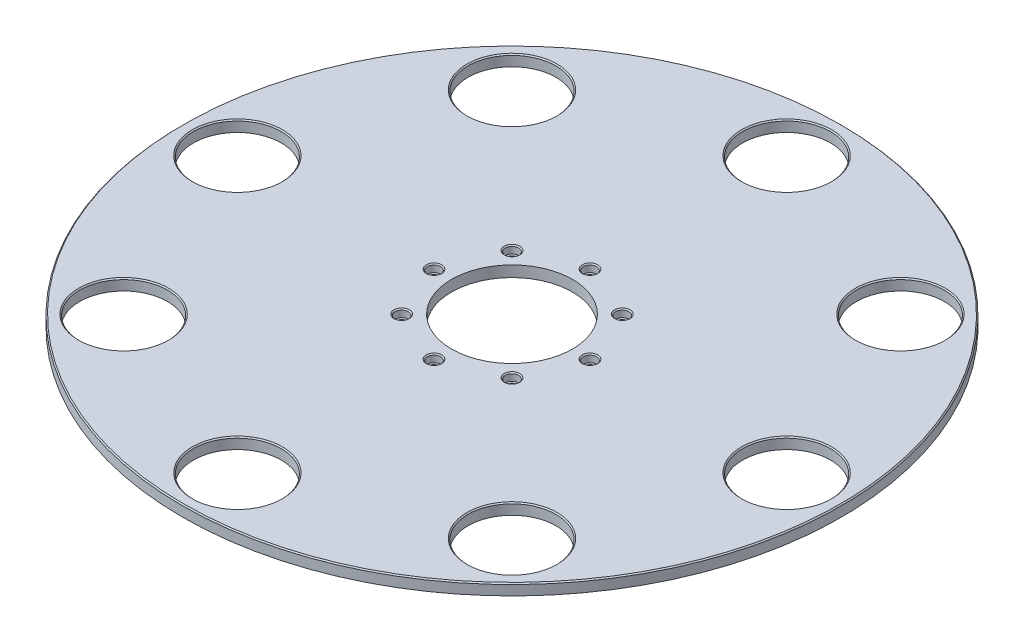
SolidWorks part; units mm, degrees
ref_plane "Front Plane" through (0, 0, 0) normal (0, 0, 1) x (1, 0, 0)
ref_plane "Top Plane" through (0, 0, 0) normal (0, 1, 0) x (1, 0, 0)
ref_plane "Right Plane" through (0, 0, 0) normal (1, 0, 0) x (0, 0, -1)
sketch "Sketch2" plane through (0, 0, 0) normal (0, 1, 0) x (1, 0, 0)
  line L0 (0, 409.7546) -> (0, -366.7272) construction
  line L1 (-380.7051, 0) -> (447.7899, 0) construction
  circle A0 centre (0, 0) radius 300
  circle A1 centre (0, 0) radius 55
  circle A2 centre (0, 250) radius 40
  circle A3 centre (176.7767, 176.7767) radius 40
  circle A4 centre (250, 0) radius 40
  circle A5 centre (176.7767, -176.7767) radius 40
  circle A6 centre (0, -250) radius 40
  circle A7 centre (-176.7767, -176.7767) radius 40
  circle A8 centre (-250, 0) radius 40
  circle A9 centre (-176.7767, 176.7767) radius 40
  point P26 (0, 0)
  point P52 (0, 0)
  dimension "D1" = 250
  dimension "D2" = 110
  dimension "D3" = 80
  dimension "D5" = 600
  dimension "D4" = 8
extrude "Boss-Extrude10" add sketch "Sketch2" along normal blind 10
chamfer "Chamfer1" distance 1 angle 45 9 edges at (-176.7767, 10, 216.7767) (0, 10, 290) (176.7767, 10, 216.7767) (250, 10, 40) (176.7767, 10, -136.7767) (0, 10, -210) (-176.7767, 10, -136.7767) (-250, 10, 40) (0, 10, 300)
sketch "Sketch13" plane through (0, 10, 0) normal (0, 1, 0) x (1, 0, 0)
  line L0 (0, 0) -> (-373.6419, 0) construction
  circle A0 centre (-71, 0) radius 6
  circle A1 centre (-50.2046, 50.2046) radius 6
  circle A2 centre (0, 71) radius 6
  circle A3 centre (50.2046, 50.2046) radius 6
  circle A4 centre (71, 0) radius 6
  circle A5 centre (50.2046, -50.2046) radius 6
  circle A6 centre (0, -71) radius 6
  circle A7 centre (-50.2046, -50.2046) radius 6
  point P6 (-64.3571, 54.9732)
  point P7 (0, 0)
  point P21 (0, 0)
  dimension "D1" = 71
  dimension "D2" = 12
  dimension "D3" = 8
extrude "Cut-Extrude1" cut sketch "Sketch13" against normal blind 7
sketch "Sketch14" plane through (0, 0, 0) normal (0, -1, 0) x (1, 0, 0)
  line L0 (0, 0) -> (-132.8482, 0) construction
  circle A0 centre (-71, 0) radius 4
  circle A1 centre (-50.2046, 50.2046) radius 4
  circle A2 centre (0, 71) radius 4
  circle A3 centre (50.2046, 50.2046) radius 4
  circle A4 centre (71, 0) radius 4
  circle A5 centre (50.2046, -50.2046) radius 4
  circle A6 centre (0, -71) radius 4
  circle A7 centre (-50.2046, -50.2046) radius 4
  point P6 (-60.629, 54.5027)
  point P7 (0, 0)
  point P21 (0, 0)
  dimension "D1" = 71
  dimension "D2" = 8
  dimension "D3" = 8
extrude "Cut-Extrude2" cut sketch "Sketch14" against normal blind 3
chamfer "Chamfer2" distance 1 angle 45 8 edges at (0, 10, 77) (50.2046, 10, 56.2046) (71, 10, 6) (50.2046, 10, -44.2046) (0, 10, -65) (-50.2046, 10, -44.2046) (-71, 10, 6) (-50.2046, 10, 56.2046)
